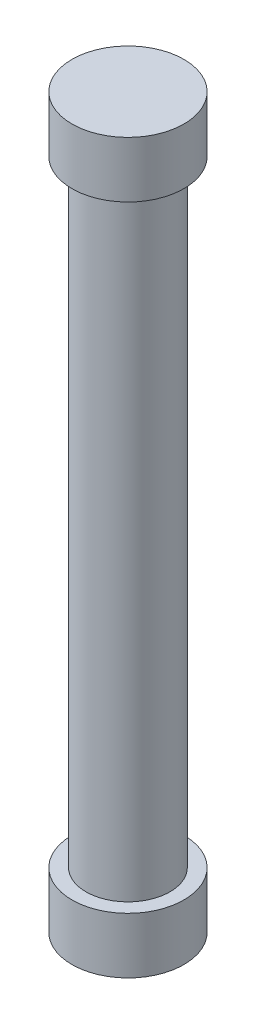
SolidWorks part; units mm, degrees
ref_plane "Front Plane" through (0, 0, 0) normal (0, 0, 1) x (1, 0, 0)
ref_plane "Top Plane" through (0, 0, 0) normal (0, 1, 0) x (1, 0, 0)
ref_plane "Right Plane" through (0, 0, 0) normal (1, 0, 0) x (0, 0, -1)
sketch "Sketch1" plane through (0, 0, 0) normal (0, 0, 1) x (1, 0, 0)
  line L0 (0, 20.9564) -> (0, -5.0436)
  line L1 (0, -5.0436) -> (-2, -5.0436)
  line L2 (-2, -5.0436) -> (-2, -3.0436)
  line L3 (-2, -3.0436) -> (-1.5, -3.0436)
  line L4 (-1.5, -3.0436) -> (-1.5, 18.9564)
  line L5 (-1.5, 18.9564) -> (-2, 18.9564)
  line L6 (-2, 18.9564) -> (-2, 20.9564)
  line L7 (-2, 20.9564) -> (0, 20.9564)
  dimension "D1" = 1.5
  dimension "D2" = 2
  dimension "D3" = 2
  dimension "D4" = 2
  dimension "D5" = 2
  dimension "D6" = 26
revolve "Revolve1" add sketch "Sketch1" angle 360 about L0
